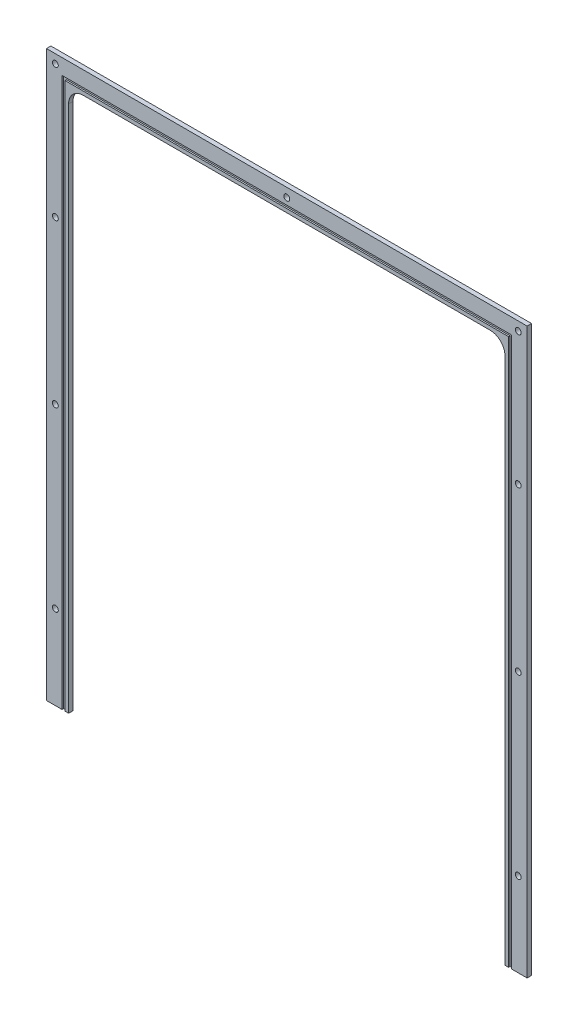
SolidWorks part; units mm, degrees
ref_plane "Front Plane" through (0, 0, 0) normal (0, 0, 1) x (1, 0, 0)
ref_plane "Top Plane" through (0, 0, 0) normal (0, 1, 0) x (1, 0, 0)
ref_plane "Right Plane" through (0, 0, 0) normal (1, 0, 0) x (0, 0, -1)
sketch "Sketch1" plane through (0, 0, 0) normal (0, 0, 1) x (1, 0, 0)
  line L0 (0, -55) -> (0, 55) construction
  line L1 (-163, 193) -> (163, 193)
  line L2 (-163, 193) -> (-163, -193)
  line L3 (-163, -193) -> (163, -193)
  line L4 (163, 193) -> (163, -193)
  line L5 (-138, 178) -> (138, 178)
  line L6 (-148, 168) -> (-148, -173)
  line L7 (-148, -173) -> (148, -173)
  line L8 (148, 168) -> (148, -173)
  line L9 (-148, -173) -> (-148, -193)
  line L10 (148, -173) -> (148, -193)
  line L11 (163, -190) -> (148, -190)
  line L12 (-148, -190) -> (-163, -190)
  circle A1 centre (-157, 187) radius 2
  circle A2 centre (157, 187) radius 2
  circle A5 centre (-157, -13) radius 2
  circle A6 centre (157, -13) radius 2
  circle A7 centre (-157, 97) radius 2
  circle A8 centre (157, 97) radius 2
  circle A9 centre (0, 187) radius 2
  circle A11 centre (-157, -133) radius 2
  circle A12 centre (157, -133) radius 2
  arc A13 (148, 168) -> (138, 178) centre (138, 168) ccw
  arc A14 (-148, 168) -> (-138, 178) centre (-138, 168) cw
  dimension "D9" = 3
  dimension "D10" = 4
  dimension "D12" = 6
  dimension "D13" = 4
  dimension "D14" = 4
  dimension "D15" = 4
  dimension "D16" = 4
  dimension "D17" = 90
  dimension "D18" = 180
  dimension "D19" = 90
  dimension "D20" = 180
  dimension "D21" = 4
  dimension "D22" = 4
  dimension "D23" = 4
  dimension "D24" = 163
  dimension "D25" = 60
  dimension "D26" = 60
  dimension "D27" = 10
  dimension "D1" = 326
  dimension "D2" = 386
  dimension "D3" = 163
  dimension "D4" = 193
  dimension "D5" = 15
  dimension "D6" = 15
  dimension "D7" = 20
  dimension "D8" = 15
  dimension "D11" = 6
  dimension "D28" = 3
extrude "Boss-Extrude1" add sketch "Sketch1" along normal blind 3
sketch "Sketch2" plane through (0, 0, 3) normal (0, 0, 1) x (1, 0, 0)
  line L0 (-148, 168) -> (-148, -190) construction
  line L2 (-150.5, -190) -> (-150.5, 180.5)
  line L4 (-152.5, -190) -> (-152.5, 182.5)
  line L6 (-152.5, 182.5) -> (152.5, 182.5)
  line L8 (-150.5, 180.5) -> (150.5, 180.5)
  line L11 (150.5, -190) -> (150.5, 180.5)
  line L13 (152.5, -190) -> (152.5, 182.5)
  line L14 (148, 168) -> (148, -190) construction
  line L15 (-138, 178) -> (138, 178) construction
  line L16 (-150.5, -190) -> (-152.5, -190)
  line L17 (152.5, -190) -> (150.5, -190)
  line M37 (148, -190) -> (163, -190)
  line M38 (-163, -190) -> (-148, -190)
  dimension "D3" = 2
  dimension "D1" = 2
  dimension "D2" = 2.5
  dimension "D4" = 2.5
  dimension "D5" = 2.5
  dimension "D6" = 2
extrude "Groove" cut sketch "Sketch2" against normal blind 1 contours L13 L6 L4 L2 L8 L11 M37 M38
